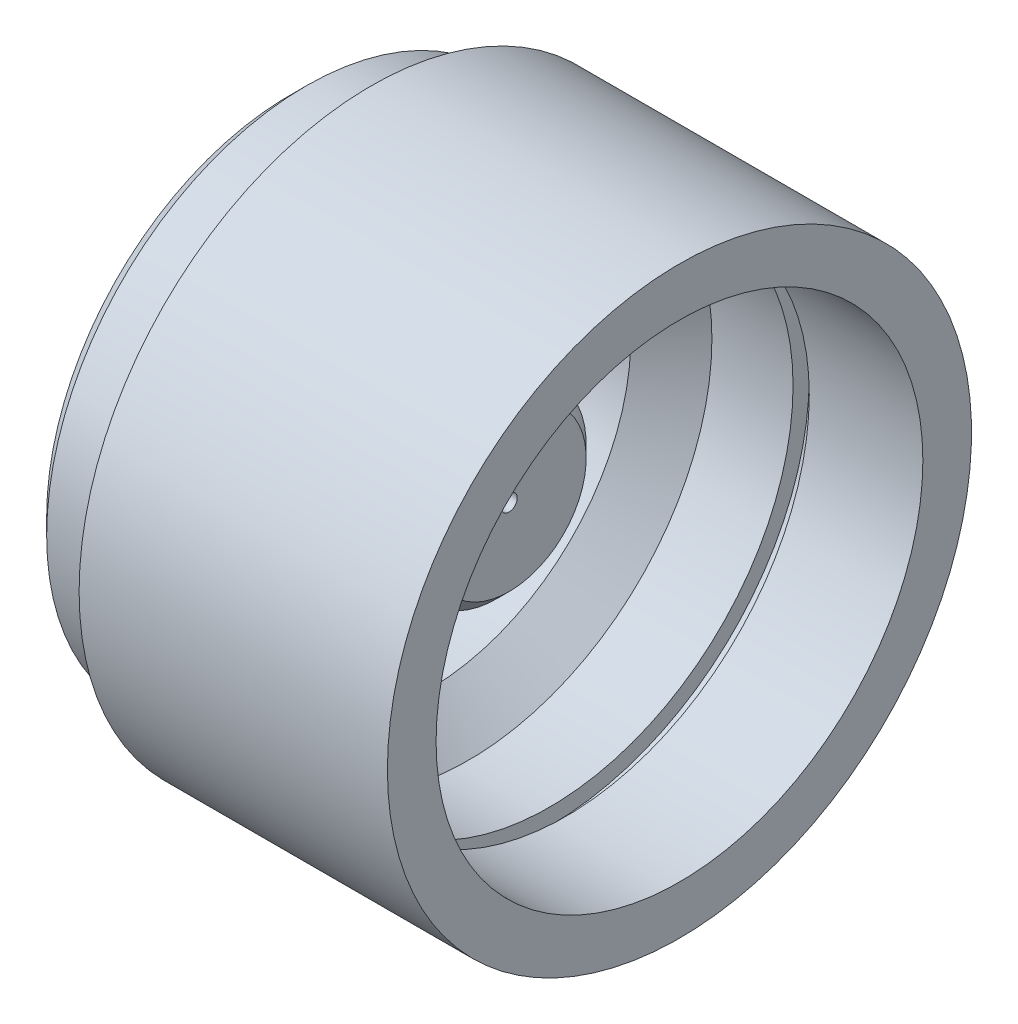
SolidWorks part; units mm, degrees
ref_plane "Plan de face" through (0, 0, 0) normal (0, 0, 1) x (1, 0, 0)
ref_plane "Plan de dessus" through (0, 0, 0) normal (0, 1, 0) x (1, 0, 0)
ref_plane "Plan de droite" through (0, 0, 0) normal (1, 0, 0) x (0, 0, -1)
sketch "Esquisse7" plane through (0, 0, 0) normal (0, 0, 1) x (1, 0, 0)
  line L0 (0, 0) -> (0, 15) construction
  line L1 (0, 15) -> (0, 18)
  line L2 (0, 18) -> (-19, 18)
  line L3 (-19, 18) -> (-19, 15)
  line L4 (-19, 15) -> (-20, 15)
  line L5 (-20, 15) -> (-20, 16)
  line L6 (-20, 16) -> (-23, 16)
  line L7 (-24, 15) -> (-24, 8)
  line L8 (-24, 8) -> (-23, 8)
  line L9 (-23, 8) -> (-23, 0)
  line L10 (-23, 0) -> (-10.5, 0)
  line L11 (-10.5, 0) -> (-10.5, 4.75)
  line L12 (-11.25, 5.5) -> (-19.75, 5.5)
  line L13 (-20.5, 6.25) -> (-20.5, 11.75)
  line L14 (0, 15) -> (-7, 15)
  line L15 (-7, 15) -> (-7, 16)
  line L16 (-7, 16) -> (-8, 16)
  line L17 (-8, 16) -> (-8, 15)
  line L18 (-8, 15) -> (-13, 15)
  line L20 (-15.5, 12.5) -> (-19.75, 12.5)
  line L21 (-15.5, 12.5) -> (-13, 15)
  line L22 (-15.5, 12.5) -> (-13, 12.5) construction
  line L23 (-13, 12.5) -> (-13, 15) construction
  line L24 (-23, 16) -> (-24, 15)
  line L25 (-19.75, 12.5) -> (-20.5, 11.75)
  line L26 (-19.75, 5.5) -> (-20.5, 6.25)
  line L27 (-10.5, 4.75) -> (-11.25, 5.5)
  line L28 (-24, 0) -> (0, 0) construction
  point P8 (-24, 16)
  point P13 (-10.5, 5.5)
  point P14 (-20.5, 5.5)
  point P15 (-20.5, 12.5)
  dimension "D1" = 15
  dimension "D2" = 3
  dimension "D3" = 19
  dimension "D4" = 3
  dimension "D5" = 1
  dimension "D6" = 1
  dimension "D7" = 4
  dimension "D8" = 8
  dimension "D9" = 1
  dimension "D10" = 8
  dimension "D11" = 12.5
  dimension "D12" = 5.5
  dimension "D13" = 10
  dimension "D14" = 7
  dimension "D15" = 7
  dimension "D16" = 1
  dimension "D17" = 1
  dimension "D18" = 5
  dimension "D19" = 5
  dimension "D20" = 2.5
revolve "Révolution2" add sketch "Esquisse7" angle 360 about L28
cosmetic thread "Représentation de filetage2" parameters "D2"=30
cosmetic thread "Représentation de filetage3" parameters "D2"=31
sketch "Esquisse18" plane through (-10.5, 0, 0) normal (1, 0, 0) x (0, 0, -1)
  point P0 (0, 0)
hole_wizard "Diamètre du perçage Ø1.0 (1)1" positions "Esquisse18" profile "Esquisse17" hole size "Ø1.0" standard "ISO"
sketch "Esquisse17" plane through (-10.5, 0, 0) normal (0, 1, 0) x (0, 0, -1)
  line L0 (0, 0) -> (0, 2.3004)
  line L1 (0, 2.3004) -> (0.5, 2)
  line L2 (0.5, 2) -> (0.5, 0)
  line L5 (0.5, 0) -> (0, 0)
  line L10 (0, 2.3004) -> (-0.5, 2) construction
  line L11 (0, -6.35) -> (0, 107.95) construction
  dimension "Diamètre du perçage" = 1
  dimension "Profondeur du perçage" = 2
  dimension "Angle de pointe" = 118
sketch "Esquisse15" plane through (-23, 0, 0) normal (-1, 0, 0) x (0, 0, 1)
  point P0 (0, 0)
hole_wizard "Diamètre du perçage Ø5.0 (5)1" positions "Esquisse15" profile "Esquisse14" hole size "Ø5.0" standard "ISO"
sketch "Esquisse14" plane through (-23, 0, 0) normal (0, 1, 0) x (0, 0, 1)
  line L0 (0, 0) -> (0, 11.0022)
  line L1 (0, 11.0022) -> (2.5, 9.5)
  line L2 (2.5, 9.5) -> (2.5, 0)
  line L5 (2.5, 0) -> (0, 0)
  line L10 (0, 11.0022) -> (-2.5, 9.5) construction
  line L11 (0, -6.35) -> (0, 107.95) construction
  dimension "Diamètre du perçage" = 5
  dimension "Profondeur du perçage" = 9.5
  dimension "Angle de pointe" = 118
cosmetic thread "Représentation de filetage4" parameters "D1"=7.5, "D2"=6
